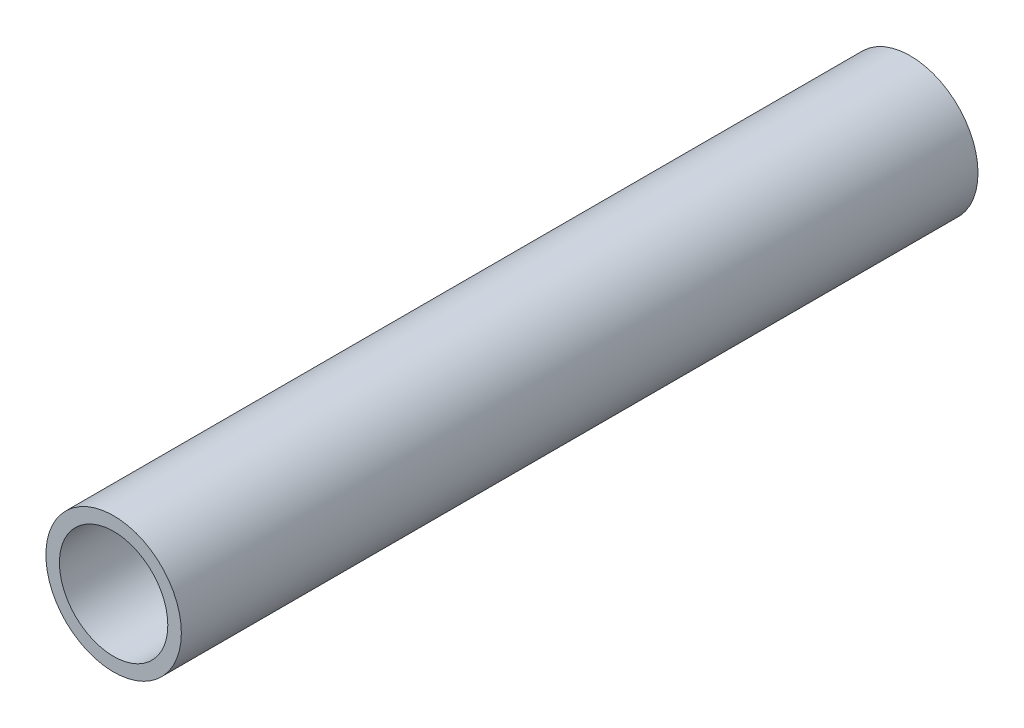
SolidWorks part; units mm, degrees
ref_plane "Спереди" through (0, 0, 0) normal (0, 0, 1) x (1, 0, 0)
ref_plane "Сверху" through (0, 0, 0) normal (0, 1, 0) x (1, 0, 0)
ref_plane "Справа" through (0, 0, 0) normal (1, 0, 0) x (0, 0, -1)
sketch "Sketch1" plane through (0, 0, 0) normal (0, 0, 1) x (1, 0, 0)
  circle A0 centre (0, 0) radius 1
  circle A1 centre (0, 0) radius 1.25
extrude "Extrude1" add sketch "Sketch1" against normal blind 14.7
